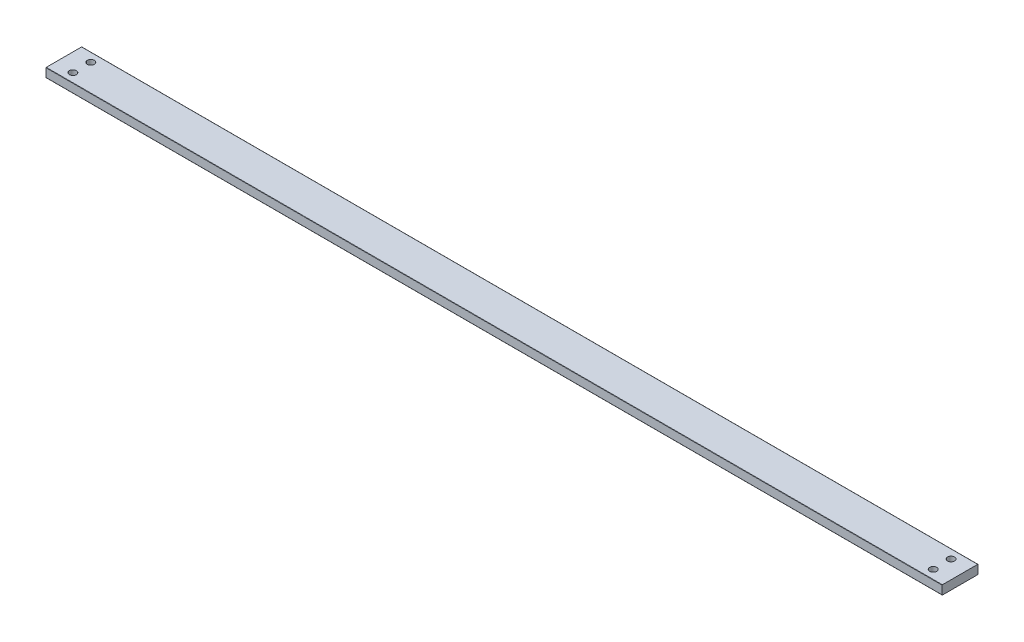
SolidWorks part; units mm, degrees
material "6061 Alloy"
ref_plane "Front Plane" through (0, 0, 0) normal (0, 0, 1) x (1, 0, 0)
ref_plane "Top Plane" through (0, 0, 0) normal (0, 1, 0) x (1, 0, 0)
ref_plane "Right Plane" through (0, 0, 0) normal (1, 0, 0) x (0, 0, -1)
sketch "Sketch1" plane through (0, 0, 0) normal (0, 1, 0) x (1, 0, 0)
  line L1 (317.5, -12.7) -> (-317.5, -12.7)
  line L2 (317.5, -12.7) -> (317.5, 12.7)
  line L3 (317.5, 12.7) -> (-317.5, 12.7)
  line L4 (-317.5, -12.7) -> (-317.5, 12.7)
  line L5 (317.5, -12.7) -> (-317.5, 12.7) construction
  line L6 (317.5, 12.7) -> (-317.5, -12.7) construction
  point P0 (0, 0)
  dimension "Length" = 635
  dimension "Width" = 25.4
sketch "Sketch2" plane through (0, 0, 0) normal (1, 0, 0) x (0, 0, -1)
  line L0 (12.7, 3.175) -> (12.7, -3.175) construction
  point P2 (12.7, 0)
  dimension "Thickness" = 6.35
sketch "Sketch3" plane through (0, 0, 0) normal (0, 1, 0) x (1, 0, 0)
  line L1 (-317.5, 12.7) -> (317.5, 12.7)
  line L2 (-317.5, 12.7) -> (-317.5, -12.7)
  line L3 (-317.5, -12.7) -> (317.5, -12.7)
  line L4 (317.5, 12.7) -> (317.5, -12.7)
extrude "Boss-Extrude1" add sketch "Sketch3" against normal up to vertex (3.175 mm away) and the other way up to vertex (3.175 mm away) up to point (0, -3.175, -12.7) other way up to point (0, 3.175, -12.7)
fillet "Fillet1" radius 0.2095 4 edges at (0, -3.175, 12.7) (0, -3.175, -12.7) (0, 3.175, -12.7) (0, 3.175, 12.7)
sketch "Sketch4" plane through (0, 3.175, 0) normal (0, 1, 0) x (1, 0, 0)
  line L0 (-317.5, 0) -> (-304.8, 0) construction
  line L1 (-317.5, 12.4904) -> (-317.5, -12.4904) construction
  line L2 (317.5, 0) -> (304.8, 0) construction
  line L3 (317.5, -12.4904) -> (317.5, 12.4904) construction
  line L4 (-304.8, 0) -> (-304.8, 6.35) construction
  line L5 (-304.8, 0) -> (-304.8, -6.35) construction
  line L6 (304.8, 0) -> (304.8, 6.35) construction
  line L7 (304.8, 0) -> (304.8, -6.35) construction
hole_wizard "#10 Clearance Hole1" positions "Sketch5" profile "Sketch6" hole size "#10" standard "ANSI Inch" end condition through all
sketch "Sketch5" plane through (0, 3.175, 0) normal (0, 1, 0) x (1, 0, 0)
  point P0 (304.8, -6.35)
  point P3 (-304.8, -6.35)
  point P11 (304.8, 6.35)
  point P14 (-304.8, 6.35)
sketch "Sketch6" plane through (304.8, 3.175, 6.35) normal (1, 0, 0) x (0, 0, 1)
  line L0 (0, 0) -> (0, 6.35)
  line L1 (0, 6.35) -> (2.4892, 6.35)
  line L2 (2.4892, 6.35) -> (2.4892, 0)
  line L5 (2.4892, 0) -> (0, 0)
  line L11 (0, -6.35) -> (0, 107.95) construction
  dimension "Thru Hole Dia." = 4.9784
  dimension "Thru Hole Depth" = 6.35
equation "\"D1@Fillet1\" = \"Thickness@Sketch2\" * .033"
